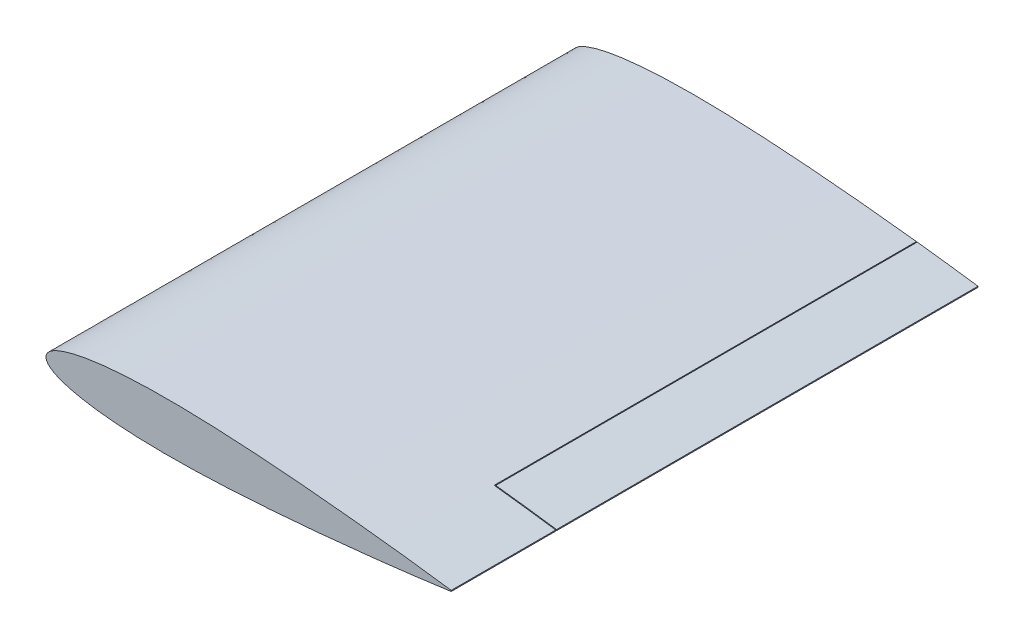
SolidWorks part; units mm, degrees
ref_plane "Front Plane" through (0, 0, 0) normal (0, 0, 1) x (1, 0, 0)
ref_plane "Top Plane" through (0, 0, 0) normal (0, 1, 0) x (1, 0, 0)
ref_plane "Right Plane" through (0, 0, 0) normal (1, 0, 0) x (0, 0, -1)
curve "Curve1"
  spline degree 3 poles (0, 0, 0) (0.003, 0.0365, 0) (0.009, 0.1114, 0) (0.0578, 0.22, 0) (0.134, 0.3245, 0) (0.2397, 0.4254, 0) (0.3736, 0.523, 0) (0.536, 0.6174, 0) (0.7264, 0.7086, 0) (0.9445, 0.7962, 0) (1.1898, 0.8801, 0) (1.462, 0.96, 0) (1.7603, 1.0355, 0) (2.0841, 1.1065, 0) (2.4327, 1.1725, 0) (2.8052, 1.2334, 0) (3.2008, 1.2888, 0) (3.6185, 1.3388, 0) (4.0575, 1.3829, 0) (4.5166, 1.4212, 0) (4.9948, 1.4535, 0) (5.491, 1.4798, 0) (6.0041, 1.5001, 0) (6.5327, 1.5144, 0) (7.0758, 1.5227, 0) (7.632, 1.5254, 0) (8.2001, 1.5224, 0) (8.7786, 1.514, 0) (9.3663, 1.5004, 0) (9.9618, 1.4819, 0) (10.5636, 1.4587, 0) (11.1705, 1.4311, 0) (11.7809, 1.3995, 0) (12.3935, 1.3642, 0) (13.0067, 1.3254, 0) (13.6193, 1.2836, 0) (14.2297, 1.2391, 0) (14.8366, 1.1921, 0) (15.4384, 1.1431, 0) (16.0339, 1.0922, 0) (16.6216, 1.0399, 0) (17.2001, 0.9864, 0) (17.7681, 0.9321, 0) (18.3242, 0.8771, 0) (18.8673, 0.8219, 0) (19.3959, 0.7666, 0) (19.9089, 0.7116, 0) (20.405, 0.657, 0) (20.8832, 0.6033, 0) (21.3422, 0.5505, 0) (21.7811, 0.499, 0) (22.1987, 0.449, 0) (22.5942, 0.4008, 0) (22.9666, 0.3545, 0) (23.3149, 0.3106, 0) (23.6385, 0.2691, 0) (23.9366, 0.2304, 0) (24.2084, 0.1946, 0) (24.4533, 0.1619, 0) (24.6708, 0.1326, 0) (24.8603, 0.1068, 0) (25.0214, 0.0847, 0) (25.1537, 0.0664, 0) (25.257, 0.052, 0) (25.3309, 0.0417, 0) (25.3753, 0.0355, 0) (25.3951, 0.0327, 0) (25.4, 0.032, 0) knots 0 0 0 0 0.004218 0.008652 0.013562 0.019137 0.0255 0.032726 0.040862 0.04993 0.05994 0.070892 0.082777 0.095581 0.109286 0.123868 0.139301 0.155557 0.172602 0.190404 0.208924 0.228125 0.247965 0.268401 0.289388 0.310881 0.332832 0.35519 0.377906 0.400928 0.424203 0.447679 0.471299 0.49501 0.518757 0.542484 0.566136 0.589657 0.612992 0.636087 0.658886 0.681338 0.703388 0.724985 0.746079 0.766619 0.786556 0.805845 0.82444 0.842296 0.859372 0.875627 0.891023 0.905523 0.919093 0.9317 0.943314 0.953909 0.963457 0.971937 0.979328 0.985613 0.990775 0.994804 0.997688 0.999422 1 1 1 1
curve "Curve2"
  spline degree 3 poles (0.0148, -0.1082, 0) (0.028, -0.1443, 0) (0.0559, -0.2205, 0) (0.1346, -0.3244, 0) (0.2395, -0.4254, 0) (0.3737, -0.523, 0) (0.536, -0.6174, 0) (0.7264, -0.7086, 0) (0.9445, -0.7962, 0) (1.1898, -0.8801, 0) (1.462, -0.96, 0) (1.7603, -1.0355, 0) (2.0841, -1.1065, 0) (2.4327, -1.1725, 0) (2.8052, -1.2334, 0) (3.2008, -1.2888, 0) (3.6185, -1.3388, 0) (4.0575, -1.3829, 0) (4.5166, -1.4212, 0) (4.9948, -1.4535, 0) (5.491, -1.4798, 0) (6.0041, -1.5001, 0) (6.5327, -1.5144, 0) (7.0758, -1.5227, 0) (7.632, -1.5254, 0) (8.2001, -1.5224, 0) (8.7786, -1.514, 0) (9.3663, -1.5004, 0) (9.9618, -1.4819, 0) (10.5636, -1.4587, 0) (11.1705, -1.4311, 0) (11.7809, -1.3995, 0) (12.3935, -1.3642, 0) (13.0067, -1.3254, 0) (13.6193, -1.2836, 0) (14.2297, -1.2391, 0) (14.8366, -1.1921, 0) (15.4384, -1.1431, 0) (16.0339, -1.0922, 0) (16.6216, -1.0399, 0) (17.2001, -0.9864, 0) (17.7681, -0.9321, 0) (18.3242, -0.8771, 0) (18.8673, -0.8219, 0) (19.3959, -0.7666, 0) (19.9089, -0.7116, 0) (20.405, -0.657, 0) (20.8832, -0.6033, 0) (21.3422, -0.5505, 0) (21.7811, -0.499, 0) (22.1987, -0.449, 0) (22.5942, -0.4008, 0) (22.9666, -0.3545, 0) (23.3149, -0.3106, 0) (23.6385, -0.2691, 0) (23.9366, -0.2304, 0) (24.2084, -0.1946, 0) (24.4533, -0.1619, 0) (24.6708, -0.1326, 0) (24.8603, -0.1068, 0) (25.0214, -0.0847, 0) (25.1537, -0.0664, 0) (25.257, -0.052, 0) (25.3309, -0.0417, 0) (25.3753, -0.0355, 0) (25.3951, -0.0327, 0) (25.4, -0.032, 0) knots 0 0 0 0 0.004453 0.009384 0.014983 0.021372 0.028629 0.036799 0.045906 0.055959 0.066957 0.078892 0.091751 0.105513 0.120157 0.135656 0.15198 0.169098 0.186975 0.205574 0.224856 0.24478 0.265302 0.286379 0.307962 0.330006 0.352459 0.375271 0.398391 0.421765 0.445339 0.46906 0.492871 0.516719 0.540546 0.564298 0.587919 0.611353 0.634545 0.657442 0.679988 0.702132 0.723821 0.745003 0.76563 0.785652 0.805023 0.823696 0.841628 0.858776 0.8751 0.890561 0.905123 0.91875 0.93141 0.943074 0.953713 0.963302 0.971818 0.979241 0.985552 0.990736 0.994782 0.997678 0.999419 1 1 1 1
sketch "Sketch1" plane through (0, 0, 0) normal (0, 0, 1) x (1, 0, 0)
  line L0 (0, 0) -> (0.0742, -0.5411)
  line L1 (127, 0.16) -> (127, -0.16)
  spline S2 degree 3 poles (0.0742, -0.5411) (0.1402, -0.7217) (0.2794, -1.1023) (0.673, -1.6219) (1.1974, -2.1272) (1.8685, -2.615) (2.6798, -3.0872) (3.6318, -3.5429) (4.7223, -3.9812) (5.9492, -4.4007) (7.31, -4.8) (8.8016, -5.1777) (10.4206, -5.5323) (12.1634, -5.8624) (14.0259, -6.1668) (16.0039, -6.4442) (18.0926, -6.6938) (20.2874, -6.9146) (22.583, -7.106) (24.9741, -7.2675) (27.4552, -7.3989) (30.0204, -7.5003) (32.6637, -7.5718) (35.3791, -7.6137) (38.1601, -7.6269) (41.0003, -7.6119) (43.8929, -7.5699) (46.8314, -7.5019) (49.8088, -7.4093) (52.8181, -7.2933) (55.8524, -7.1556) (58.9045, -6.9976) (62.9897, -6.7619) (67.0743, -6.4928) (72.1532, -6.1221) (77.1616, -5.7236) (82.1152, -5.2913) (86.9285, -4.8463) (91.5567, -4.3963) (96.0742, -3.9303) (100.3424, -3.4723) (104.3213, -3.0299) (108.8003, -2.5098) (112.8562, -2.0199) (115.9539, -1.6325) (118.1927, -1.3456) (120.4545, -1.0515) (122.9821, -0.715) (125.1839, -0.4131) (126.3836, -0.2463) (126.7779, -0.1912) (127, -0.16) knots 0 0 0 0 0.004453 0.009384 0.014983 0.021372 0.028629 0.036799 0.045906 0.055959 0.066957 0.078892 0.091751 0.105513 0.120157 0.135656 0.15198 0.169098 0.186975 0.205574 0.224856 0.24478 0.265302 0.286379 0.307962 0.330006 0.352459 0.375271 0.398391 0.421765 0.445339 0.46906 0.492871 0.540546 0.564298 0.611353 0.657442 0.679988 0.723821 0.76563 0.785652 0.823696 0.858776 0.890561 0.91875 0.93141 0.943074 0.971818 0.990736 0.994782 1 1 1 1
  spline S3 degree 3 poles (0, 0) (0.0148, 0.1826) (0.0451, 0.5571) (0.2892, 1.1001) (0.6698, 1.6226) (1.1984, 2.127) (1.8682, 2.615) (2.6799, 3.0872) (3.6318, 3.5429) (4.7223, 3.9812) (5.9492, 4.4007) (7.31, 4.8) (8.8016, 5.1777) (10.4206, 5.5323) (12.1634, 5.8624) (14.0259, 6.1668) (16.0039, 6.4442) (18.0926, 6.6938) (20.2874, 6.9146) (22.583, 7.106) (24.9741, 7.2675) (27.4552, 7.3989) (30.0204, 7.5003) (32.6637, 7.5718) (35.3791, 7.6137) (38.1601, 7.6269) (41.0003, 7.6119) (43.8929, 7.5699) (46.8314, 7.5019) (49.8088, 7.4093) (52.8181, 7.2933) (55.8524, 7.1556) (58.9045, 6.9976) (62.9897, 6.7619) (67.0743, 6.4928) (72.1532, 6.1221) (77.1616, 5.7236) (82.1152, 5.2913) (86.9285, 4.8463) (91.5567, 4.3963) (96.0742, 3.9303) (100.3424, 3.4723) (104.3213, 3.0299) (108.8003, 2.5098) (112.8562, 2.0199) (115.9539, 1.6325) (118.1927, 1.3456) (120.4545, 1.0515) (122.9821, 0.715) (125.1839, 0.4131) (126.3836, 0.2463) (126.7779, 0.1912) (127, 0.16) knots 0 0 0 0 0.004218 0.008652 0.013562 0.019137 0.0255 0.032726 0.040862 0.04993 0.05994 0.070892 0.082777 0.095581 0.109286 0.123868 0.139301 0.155557 0.172602 0.190404 0.208924 0.228125 0.247965 0.268401 0.289388 0.310881 0.332832 0.35519 0.377906 0.400928 0.424203 0.447679 0.471299 0.49501 0.542484 0.566136 0.612992 0.658886 0.681338 0.724985 0.766619 0.786556 0.82444 0.859372 0.891023 0.919093 0.9317 0.943314 0.971937 0.990775 0.994804 1 1 1 1
  point P0 (127, 0)
  dimension "D1" = 127
extrude "Boss-Extrude1" add sketch "Sketch1" along normal blind 165.1
sketch "Sketch2" plane through (0, 0, 0) normal (0, 1, 0) x (1, 0, 0)
  line L0 (127, -165.1) -> (127, 0) construction
  line L1 (107.95, 0) -> (127, 0)
  line L2 (107.95, 0) -> (107.95, -132.08)
  line L3 (107.95, -132.08) -> (127, -132.08)
  line L4 (127, 0) -> (127, -132.08)
  dimension "D1" = 132.08
  dimension "D2" = 19.05
extrude "Cut-Extrude-Thin1" cut sketch "Sketch2" against normal blind 25.4 and the other way blind 25.4 thin thin type one direction wall 0.254
equation "\"span\" = 48"
equation "\"wing_chord\"= 9"
equation "\"fuse_len\"= 15"
equation "\"fuse_height\"= 5"
equation "\"fuse_wid\"= 5"
equation "\"foam_t\"= 0.1875"
equation "\"main_spar_len\"= 36"
equation "\"x_fuse_to_wing\"= 3"
equation "\"x_cg_from_le\"= 2.25"
equation "\"boom_len\"= 36"
equation "\"wing_angle\"= 1.5"
equation "\"boom_d\"= 0.75"
equation "\"wing_spar_d\"= 0.5"
equation "\"wing_spar_l\"= 48"
equation "\"wing_spar_spacing\"= 1.35"
equation "\"wing_mount_l\" = 2.5"
equation "\"vstab_span\"= 6.5"
equation "\"hstab_span\"= 15.25"
equation "\"tail_chord\"= 5"
equation "\"D1@Boss-Extrude1\"= \"vstab_span\""
equation "\"D1@Sketch2\"=\"vstab_span\"*0.8"
equation "\"D2@Sketch2\"=\"tail_chord\"*0.15"
